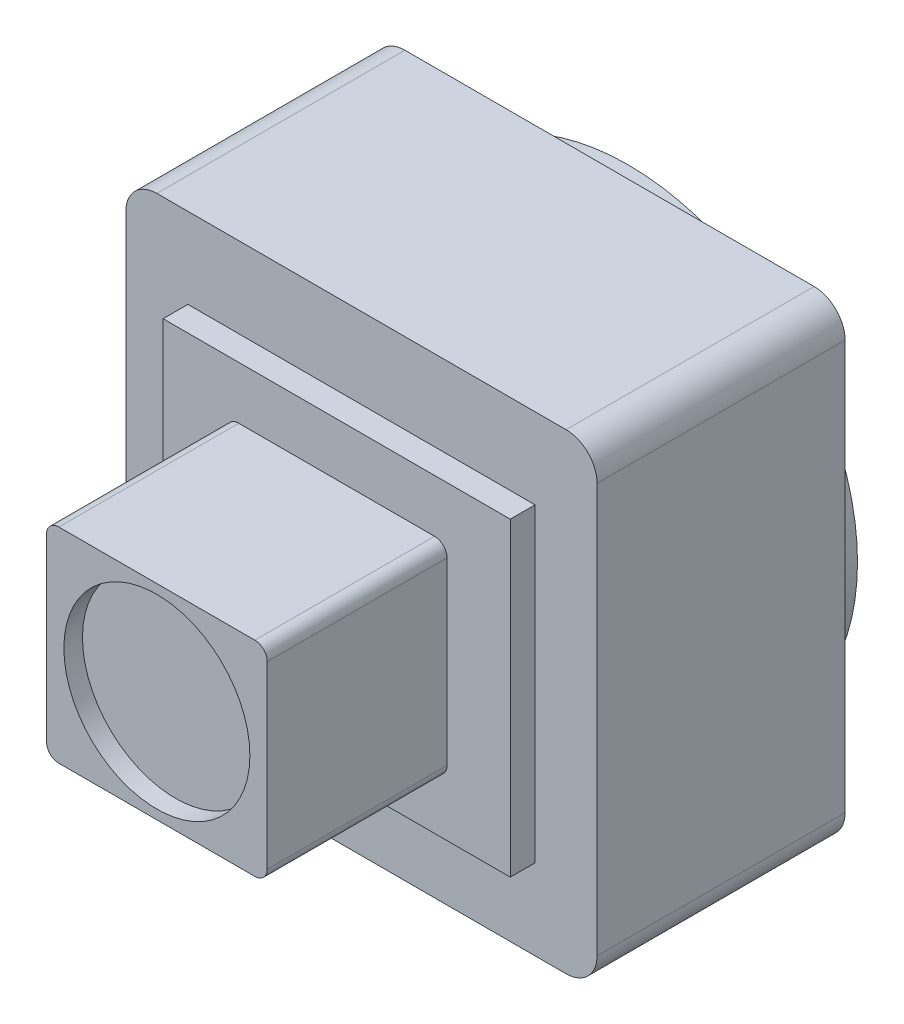
SolidWorks part; units mm, degrees
ref_plane "Front" through (0, 0, 0) normal (0, 0, 1) x (1, 0, 0)
ref_plane "Top" through (0, 0, 0) normal (0, 1, 0) x (1, 0, 0)
ref_plane "Right" through (0, 0, 0) normal (1, 0, 0) x (0, 0, -1)
sketch "Sketch1" plane through (0, 0, 0) normal (0, 0, 1) x (1, 0, 0)
  line L1 (-48.26, 48.26) -> (48.26, 48.26)
  line L2 (-48.26, 48.26) -> (-48.26, -48.26)
  line L3 (-48.26, -48.26) -> (48.26, -48.26)
  line L4 (48.26, 48.26) -> (48.26, -48.26)
  line L5 (-48.26, 48.26) -> (48.26, -48.26) construction
  line L6 (-48.26, -48.26) -> (48.26, 48.26) construction
  point P0 (0, 0)
  dimension "D1" = 96.52
  dimension "D2" = 96.52
extrude "Boss-Extrude1" add sketch "Sketch1" along normal blind 50.8
sketch "Sketch2" plane through (0, 0, 50.8) normal (0, 0, 1) x (1, 0, 0)
  line L1 (-35.56, 31.75) -> (35.56, 31.75)
  line L2 (-35.56, 31.75) -> (-35.56, -31.75)
  line L3 (-35.56, -31.75) -> (35.56, -31.75)
  line L4 (35.56, 31.75) -> (35.56, -31.75)
  line L5 (-35.56, 31.75) -> (35.56, -31.75) construction
  line L6 (-35.56, -31.75) -> (35.56, 31.75) construction
  point P0 (0, 0)
  dimension "D1" = 63.5
  dimension "D2" = 71.12
extrude "Boss-Extrude2" add sketch "Sketch2" along normal blind 5.08
sketch "Sketch3" plane through (0, 0, 55.88) normal (0, 0, 1) x (1, 0, 0)
  line L1 (-22.606, 20.955) -> (22.606, 20.955)
  line L2 (-22.606, 20.955) -> (-22.606, -20.955)
  line L3 (-22.606, -20.955) -> (22.606, -20.955)
  line L4 (22.606, 20.955) -> (22.606, -20.955)
  line L5 (-22.606, 20.955) -> (22.606, -20.955) construction
  line L6 (-22.606, -20.955) -> (22.606, 20.955) construction
  point P0 (0, 0)
  dimension "D1" = 41.91
  dimension "D2" = 45.212
extrude "Boss-Extrude3" add sketch "Sketch3" along normal blind 36.83
sketch "Sketch4" plane through (0, 0, 92.71) normal (0, 0, 1) x (1, 0, 0)
  circle A0 centre (0, 0) radius 19.05
  dimension "D1" = 38.1
extrude "Cut-Extrude1" cut sketch "Sketch4" against normal blind 3.81
sketch "Sketch5" plane through (0, 0, 0) normal (0, 0, -1) x (-1, 0, 0)
  circle A0 centre (0, 0) radius 46.99
  dimension "D1" = 93.98
extrude "Boss-Extrude4" add sketch "Sketch5" along normal blind 3.81
fillet "Fillet1" radius 2.54 4 edges at (-22.606, -20.955, 74.295) (-22.606, 20.955, 74.295) (22.606, -20.955, 74.295) (22.606, 20.955, 74.295)
fillet "Fillet2" radius 6.35 4 edges at (48.26, 48.26, 25.4) (48.26, -48.26, 25.4) (-48.26, -48.26, 25.4) (-48.26, 48.26, 25.4)
